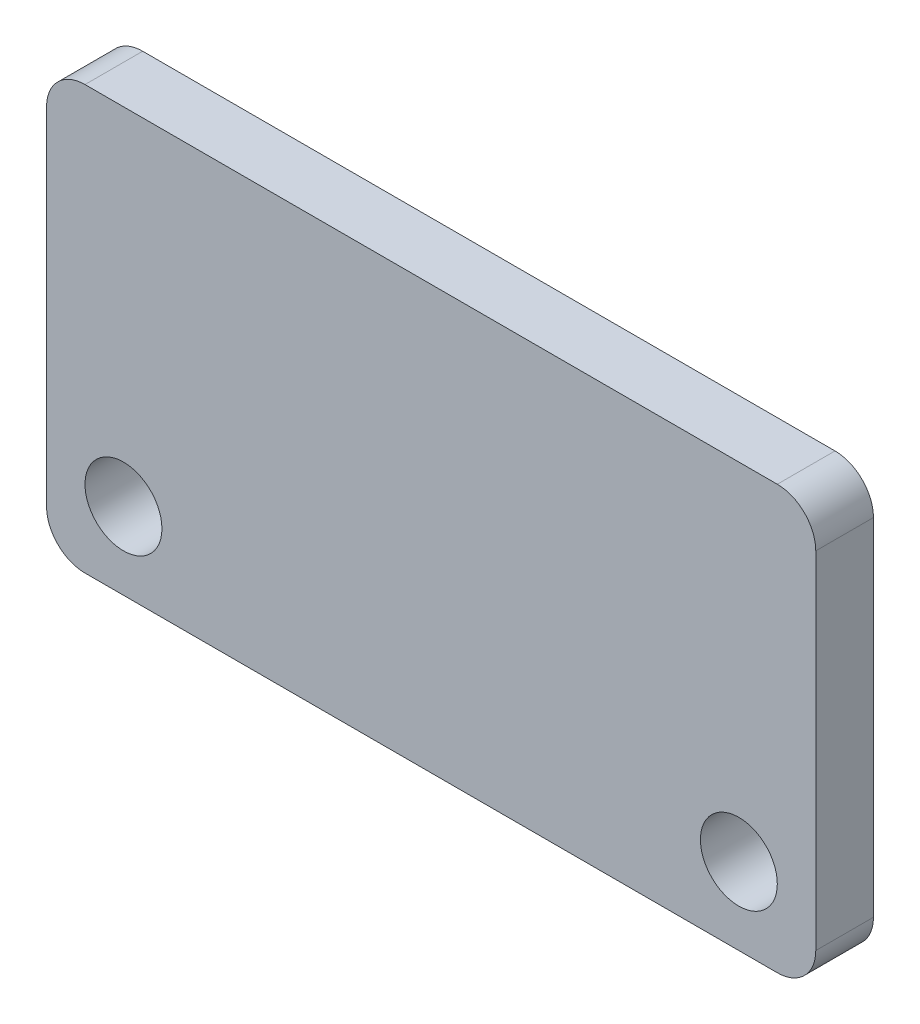
SolidWorks part; units mm, degrees
ref_plane "Płaszczyzna przednia" through (0, 0, 0) normal (0, 0, 1) x (1, 0, 0)
ref_plane "Płaszczyzna górna" through (0, 0, 0) normal (0, 1, 0) x (1, 0, 0)
ref_plane "Płaszczyzna prawa" through (0, 0, 0) normal (1, 0, 0) x (0, 0, -1)
sketch "Szkic1" plane through (0, 0, 0) normal (0, 0, 1) x (1, 0, 0)
  line L1 (-10, 5.5) -> (10, 5.5)
  line L2 (-10, 5.5) -> (-10, -5.5)
  line L3 (-10, -5.5) -> (10, -5.5)
  line L4 (10, 5.5) -> (10, -5.5)
  line L5 (-10, 5.5) -> (10, -5.5) construction
  line L6 (-10, -5.5) -> (10, 5.5) construction
  point P0 (0, 0)
  dimension "D1" = 20
  dimension "D2" = 11
extrude "Dodanie-wyciągnięcie1" add sketch "Szkic1" along normal blind 1.5
fillet "Zaokrąglenie1" radius 1 4 edges at (10, -5.5, 0.75) (-10, 5.5, 0.75) (10, 5.5, 0.75) (-10, -5.5, 0.75)
hole_wizard "Otwory ustalające Ø2.0mm1" positions "Szkic2" profile "Szkic3" hole size "Ø2.0" standard "Ansi Metric"
sketch "Szkic2" plane through (0, 0, 1.5) normal (0, 0, 1) x (1, 0, 0)
  line L0 (-9, -5.5) -> (9, -5.5) construction
  line L1 (-10, 4.5) -> (-10, -4.5) construction
  point P0 (-8, -3.5)
  point P2 (8, -3.5)
  dimension "D1" = 16
  dimension "D2" = 2
  dimension "D3" = 2
sketch "Szkic3" plane through (-8, -3.5, 1.5) normal (1, 0, 0) x (0, -1, 0)
  line L0 (0, 0) -> (0, 2.6009)
  line L1 (0, 2.6009) -> (1, 2)
  line L2 (1, 2) -> (1, 0)
  line L5 (1, 0) -> (0, 0)
  line L10 (0, 2.6009) -> (-1, 2) construction
  line L11 (0, -6.35) -> (0, 107.95) construction
  dimension "Średnica otworu" = 2
  dimension "Głębokość otworu" = 2
  dimension "Kąt wiertła" = 118
